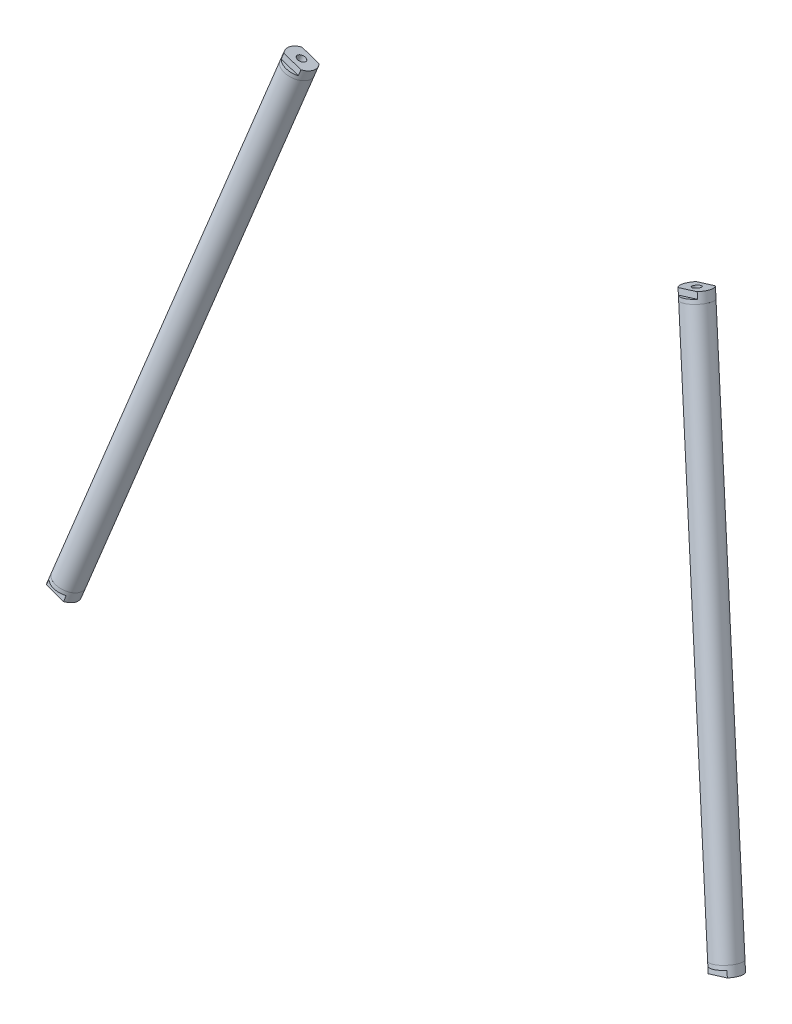
SolidWorks part; units mm, degrees
material "Thornel Mat VMA"
ref_plane "Front Plane" through (0, 0, 0) normal (0, 0, 1) x (1, 0, 0)
ref_plane "Top Plane" through (0, 0, 0) normal (0, 1, 0) x (1, 0, 0)
ref_plane "Right Plane" through (0, 0, 0) normal (1, 0, 0) x (0, 0, -1)
sketch3d "3DSketch2"
  line L0 (283.5348, 590.1447, -1192.1134) -> (176.7997, 969.6398, -1274.8208) construction
ref_plane "Plane1" through (283.5348, 590.1447, -1192.1134) normal (-0.265, 0.9421, -0.2053) x (0.9643, 0.2589, -0.0564)
ref_plane "Plane2" through (270.0737, 638.0053, -1202.5442) normal (-0.265, 0.9421, -0.2053) x (0.9643, 0.2589, -0.0564)
sketch "Sketch2" plane through (270.0737, 638.0053, -1202.5442) normal (-0.265, 0.9421, -0.2053) x (0.9643, 0.2589, -0.0564)
  circle A0 centre (0, 0) radius 7.62
  circle A1 centre (0, 0) radius 9.017
  dimension "D1" = 15.24
  dimension "D2" = 18.034
extrude "Boss-Extrude1" add sketch "Sketch2" along normal blind 331.47
sketch "Sketch3" plane through (-293.5766, 1043.8072, -227.4879) normal (-0.265, 0.9421, -0.2053) x (0.9643, 0.2589, -0.0564)
  circle A0 centre (493.4562, 1039.1054) radius 9.017 construction
  circle A2 centre (493.4562, 1039.1054) radius 9.017
extrude "Boss-Extrude2" add sketch "Sketch3" along normal blind 6.35 separate body
sketch "Sketch4" plane through (-293.5766, 1043.8072, -227.4879) normal (-0.265, 0.9421, -0.2053) x (0.9643, 0.2589, -0.0564)
  circle A1 centre (493.4562, 1039.1054) radius 7.62 construction
  circle A2 centre (493.4562, 1039.1054) radius 7.62
extrude "Boss-Extrude3" add sketch "Sketch4" against normal blind 12.7
sketch "Sketch7" plane through (-295.2592, 1049.7898, -228.7918) normal (-0.265, 0.9421, -0.2053) x (0.9643, 0.2589, -0.0564)
  line L0 (487.0544, 1045.4554) -> (487.0544, 1050.5354)
  line L1 (487.0544, 1045.4554) -> (499.8581, 1045.4554)
  line L2 (487.0544, 1050.5354) -> (499.8581, 1050.5354)
  line L3 (487.0544, 1032.7554) -> (499.8581, 1032.7554)
  line L4 (499.8581, 1050.5354) -> (499.8581, 1045.4554)
  line L5 (487.0544, 1045.4554) -> (499.8581, 1032.7554) construction
  line L6 (487.0544, 1032.7554) -> (499.8581, 1045.4554) construction
  line L7 (487.0544, 1032.7554) -> (487.0544, 1027.6754)
  line L8 (487.0544, 1027.6754) -> (499.8581, 1027.6754)
  line L9 (499.8581, 1027.6754) -> (499.8581, 1032.7554)
  circle A0 centre (493.4562, 1039.1054) radius 9.017 construction
  point P0 (493.4562, 1039.1054)
  dimension "D1" = 12.7
  dimension "D2" = 5.08
  dimension "D3" = 5.08
extrude "Cut-Extrude1" cut sketch "Sketch7" against normal blind 3.81
ref_plane "Plane3" through (-249.6599, 887.6619, -193.4576) normal (-0.265, 0.9421, -0.2053) x (0.9643, 0.2589, -0.0564)
mirror "Mirror1" about plane through (-249.6599, 887.6619, -193.4576) normal (-0.265, 0.9421, -0.2053) of bodies 119 112
hole_wizard "1/4-28 Tapped Hole1" positions "Sketch6" profile "Sketch5" tap size "1/4-28" standard "ANSI Inch" end condition through all
sketch "Sketch6" plane through (-295.2592, 1049.7898, -228.7918) normal (-0.265, 0.9421, -0.2053) x (0.9643, 0.2589, -0.0564)
  point P0 (493.4562, 1039.1054)
sketch "Sketch5" plane through (180.5577, 956.2784, -1271.9088) normal (0.6668, 0.3329, 0.6668) x (-0.6965, -0.0398, 0.7164)
  line L0 (0, 0) -> (0, 350.9731)
  line L1 (0, 350.9731) -> (2.7051, 350.9731)
  line L2 (2.7051, 350.9731) -> (2.7051, 0)
  line L5 (2.7051, 0) -> (0, 0)
  line L11 (0, -6.35) -> (0, 107.95) construction
  dimension "Thru Tap Drill Dia." = 5.4102
  dimension "Thru Tap Drill Depth" = 350.9731
cosmetic thread "Hole Thread1" parameters "D2"=6.35
ref_plane "Plane4" through (45.8284, 0, 0) normal (1, 0, 0) x (0, 0, -1)
mirror "Mirror2" about plane through (45.8284, 0, 0) normal (1, 0, 0) of bodies 115 114 110
